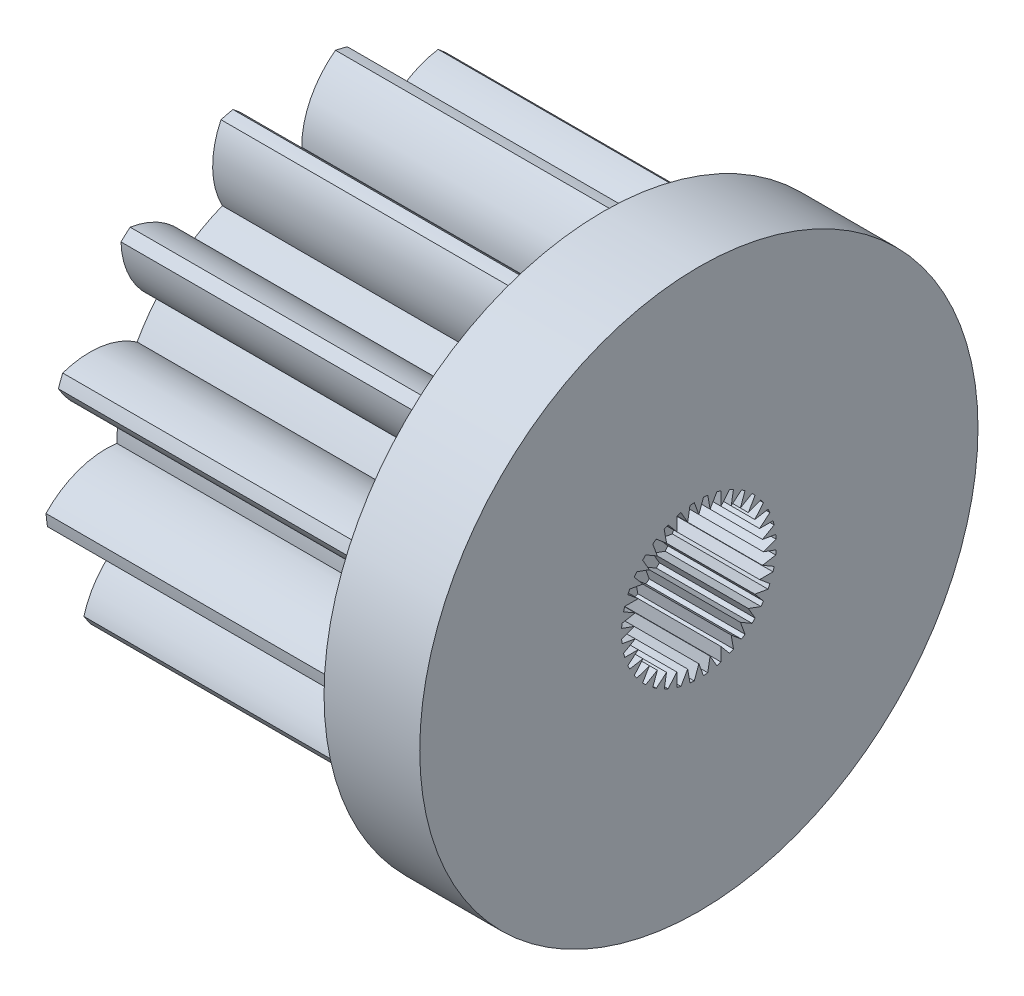
SolidWorks part; units mm, degrees
ref_plane "Front Plane" through (0, 0, 0) normal (0, 0, 1) x (1, 0, 0)
ref_plane "Top Plane" through (0, 0, 0) normal (0, 1, 0) x (1, 0, 0)
ref_plane "Right Plane" through (0, 0, 0) normal (1, 0, 0) x (0, 0, -1)
ref_plane "Plane1" through (0, 0, 0) normal (0, 0, -1) x (-1, 0, 0)
sketch "Sketch1" plane through (0, 0, 0) normal (0, 0, -1) x (-1, 0, 0)
  line L0 (-13, 8.75) -> (-13, 0)
  line L1 (-13, 0) -> (-10, 0)
  line L2 (-10, 0) -> (-10, 8.75)
  line L3 (-10, 8.75) -> (-13, 8.75)
  line L4 (-13, 0) -> (-10, 0) construction
revolve "Revolve1" add sketch "Sketch1" angle 360 about L4
sketch "Sketch2" plane through (10, 0, 0) normal (-1, 0, 0) x (0, 0, 1)
  arc A0 (3.9833, 3.4184) -> (4.6087, 2.5123) centre (0, 0) cw
  arc A1 (4.6087, 2.5123) -> (6.9422, 2.8383) centre (6.0962, 0.3798) cw
  arc A2 (6.9422, 2.8383) -> (7.0785, 2.479) centre (0, 0) cw
  arc A3 (7.0785, 2.479) -> (5.1156, 1.1757) centre (4.8149, 3.7582) cw
  arc A4 (5.1156, 1.1757) -> (5.2483, 0.0827) centre (0, 0) cw
  arc A5 (5.2483, 0.0827) -> (7.466, -0.713) centre (5.5744, -2.4967) cw
  arc A6 (7.466, -0.713) -> (7.4197, -1.0945) centre (0, 0) cw
  arc A7 (7.4197, -1.0945) -> (5.076, -1.3363) centre (6.0099, 1.0901) cw
  arc A8 (5.076, -1.3363) -> (4.6856, -2.3658) centre (0, 0) cw
  arc A9 (4.6856, -2.3658) -> (6.2795, -4.101) centre (3.7756, -4.8013) cw
  arc A10 (6.2795, -4.101) -> (6.0612, -4.4172) centre (0, 0) cw
  arc A11 (6.0612, -4.4172) -> (3.8736, -3.5422) centre (5.8281, -1.8277) cw
  arc A12 (3.8736, -3.5422) -> (3.0495, -4.2723) centre (0, 0) cw
  arc A13 (3.0495, -4.2723) -> (3.6544, -6.5495) centre (1.1118, -6.006) cw
  arc A14 (3.6544, -6.5495) -> (3.3142, -6.728) centre (0, 0) cw
  arc A15 (3.3142, -6.728) -> (1.7837, -4.9366) centre (4.3112, -4.3268) cw
  arc A16 (1.7837, -4.9366) -> (0.7147, -5.2001) centre (0, 0) cw
  arc A17 (0.7147, -5.2001) -> (0.1921, -7.4975) centre (-1.8066, -5.8347) cw
  arc A18 (0.1921, -7.4975) -> (-0.1921, -7.4975) centre (0, 0) cw
  arc A19 (-0.1921, -7.4975) -> (-0.7147, -5.2001) centre (1.8066, -5.8347) cw
  arc A20 (-0.7147, -5.2001) -> (-1.7837, -4.9366) centre (0, 0) cw
  arc A21 (-1.7837, -4.9366) -> (-3.3142, -6.728) centre (-4.3112, -4.3268) cw
  arc A22 (-3.3142, -6.728) -> (-3.6544, -6.5495) centre (0, 0) cw
  arc A23 (-3.6544, -6.5495) -> (-3.0495, -4.2723) centre (-1.1118, -6.006) cw
  arc A24 (-3.0495, -4.2723) -> (-3.8736, -3.5422) centre (0, 0) cw
  arc A25 (-3.8736, -3.5422) -> (-6.0612, -4.4172) centre (-5.8281, -1.8277) cw
  arc A26 (-6.0612, -4.4172) -> (-6.2795, -4.101) centre (0, 0) cw
  arc A27 (-6.2795, -4.101) -> (-4.6856, -2.3658) centre (-3.7756, -4.8013) cw
  arc A28 (-4.6856, -2.3658) -> (-5.076, -1.3363) centre (0, 0) cw
  arc A29 (-5.076, -1.3363) -> (-7.4197, -1.0945) centre (-6.0099, 1.0901) cw
  arc A30 (-7.4197, -1.0945) -> (-7.466, -0.713) centre (0, 0) cw
  arc A31 (-7.466, -0.713) -> (-5.2483, 0.0827) centre (-5.5744, -2.4967) cw
  arc A32 (-5.2483, 0.0827) -> (-5.1156, 1.1757) centre (0, 0) cw
  arc A33 (-5.1156, 1.1757) -> (-7.0785, 2.479) centre (-4.8149, 3.7582) cw
  arc A34 (-7.0785, 2.479) -> (-6.9422, 2.8383) centre (0, 0) cw
  arc A35 (-6.9422, 2.8383) -> (-4.6087, 2.5123) centre (-6.0962, 0.3798) cw
  arc A36 (-4.6087, 2.5123) -> (-3.9833, 3.4184) centre (0, 0) cw
  arc A37 (-3.9833, 3.4184) -> (-5.1156, 5.4846) centre (-2.5169, 5.5654) cw
  arc A38 (-5.1156, 5.4846) -> (-4.828, 5.7394) centre (0, 0) cw
  arc A39 (-4.828, 5.7394) -> (-2.9133, 4.3663) centre (-5.2214, 3.1693) cw
  arc A40 (-2.9133, 4.3663) -> (-1.9384, 4.878) centre (0, 0) cw
  arc A41 (-1.9384, 4.878) -> (-1.9808, 7.2337) centre (0.3578, 6.0975) cw
  arc A42 (-1.9808, 7.2337) -> (-1.6077, 7.3257) centre (0, 0) cw
  arc A43 (-1.6077, 7.3257) -> (-0.5505, 5.2201) centre (-3.1505, 5.2328) cw
  arc A44 (-0.5505, 5.2201) -> (0.5505, 5.2201) centre (0, 0) cw
  arc A45 (0.5505, 5.2201) -> (1.6077, 7.3257) centre (3.1505, 5.2328) cw
  arc A46 (1.6077, 7.3257) -> (1.9808, 7.2337) centre (0, 0) cw
  arc A47 (1.9808, 7.2337) -> (1.9384, 4.878) centre (-0.3578, 6.0975) cw
  arc A48 (1.9384, 4.878) -> (2.9133, 4.3663) centre (0, 0) cw
  arc A49 (2.9133, 4.3663) -> (4.828, 5.7394) centre (5.2214, 3.1693) cw
  arc A50 (4.828, 5.7394) -> (5.1156, 5.4846) centre (0, 0) cw
  arc A51 (5.1156, 5.4846) -> (3.9833, 3.4184) centre (2.5169, 5.5654) cw
extrude "Boss-Extrude1" add sketch "Sketch2" along normal blind 10
sketch "Sketch3" plane through (13, 0, 0) normal (1, 0, 0) x (0, 0, -1)
  line L0 (0, -2.025) -> (0.144, -2.4207)
  line L1 (0.2785, -2.409) -> (0.3516, -1.9942)
  line L2 (0.3516, -1.9942) -> (0.5622, -2.3589)
  line L3 (0.6926, -2.324) -> (0.6926, -1.9029)
  line L4 (0.6926, -1.9029) -> (0.9633, -2.2255)
  line L5 (1.0856, -2.1684) -> (1.0125, -1.7537)
  line L6 (1.0125, -1.7537) -> (1.3351, -2.0244)
  line L7 (1.4457, -1.947) -> (1.3016, -1.5512)
  line L8 (1.3016, -1.5512) -> (1.6663, -1.7618)
  line L9 (1.7618, -1.6663) -> (1.5512, -1.3016)
  line L10 (1.5512, -1.3016) -> (1.947, -1.4457)
  line L11 (2.0244, -1.3351) -> (1.7537, -1.0125)
  line L12 (1.7537, -1.0125) -> (2.1684, -1.0856)
  line L13 (2.2255, -0.9633) -> (1.9029, -0.6926)
  line L14 (1.9029, -0.6926) -> (2.324, -0.6926)
  line L15 (2.3589, -0.5622) -> (1.9942, -0.3516)
  line L16 (1.9942, -0.3516) -> (2.409, -0.2785)
  line L17 (2.4207, -0.144) -> (2.025, 0)
  line L18 (2.025, 0) -> (2.4207, 0.144)
  line L19 (2.409, 0.2785) -> (1.9942, 0.3516)
  line L20 (1.9942, 0.3516) -> (2.3589, 0.5622)
  line L21 (2.324, 0.6926) -> (1.9029, 0.6926)
  line L22 (1.9029, 0.6926) -> (2.2255, 0.9633)
  line L23 (2.1684, 1.0856) -> (1.7537, 1.0125)
  line L24 (1.7537, 1.0125) -> (2.0244, 1.3351)
  line L25 (1.947, 1.4457) -> (1.5512, 1.3016)
  line L26 (1.5512, 1.3016) -> (1.7618, 1.6663)
  line L27 (1.6663, 1.7618) -> (1.3016, 1.5512)
  line L28 (1.3016, 1.5512) -> (1.4457, 1.947)
  line L29 (1.3351, 2.0244) -> (1.0125, 1.7537)
  line L30 (1.0125, 1.7537) -> (1.0856, 2.1684)
  line L31 (0.9633, 2.2255) -> (0.6926, 1.9029)
  line L32 (0.6926, 1.9029) -> (0.6926, 2.324)
  line L33 (0.5622, 2.3589) -> (0.3516, 1.9942)
  line L34 (0.3516, 1.9942) -> (0.2785, 2.409)
  line L35 (0.144, 2.4207) -> (0, 2.025)
  line L36 (0, 2.025) -> (-0.144, 2.4207)
  line L37 (-0.2785, 2.409) -> (-0.3516, 1.9942)
  line L38 (-0.3516, 1.9942) -> (-0.5622, 2.3589)
  line L39 (-0.6926, 2.324) -> (-0.6926, 1.9029)
  line L40 (-0.6926, 1.9029) -> (-0.9633, 2.2255)
  line L41 (-1.0856, 2.1684) -> (-1.0125, 1.7537)
  line L42 (-1.0125, 1.7537) -> (-1.3351, 2.0244)
  line L43 (-1.4457, 1.947) -> (-1.3016, 1.5512)
  line L44 (-1.3016, 1.5512) -> (-1.6663, 1.7618)
  line L45 (-1.7618, 1.6663) -> (-1.5512, 1.3016)
  line L46 (-1.5512, 1.3016) -> (-1.947, 1.4457)
  line L47 (-2.0244, 1.3351) -> (-1.7537, 1.0125)
  line L48 (-1.7537, 1.0125) -> (-2.1684, 1.0856)
  line L49 (-2.2255, 0.9633) -> (-1.9029, 0.6926)
  line L50 (-1.9029, 0.6926) -> (-2.324, 0.6926)
  line L51 (-2.3589, 0.5622) -> (-1.9942, 0.3516)
  line L52 (-1.9942, 0.3516) -> (-2.409, 0.2785)
  line L53 (-2.4207, 0.144) -> (-2.025, 0)
  line L54 (-2.025, 0) -> (-2.4207, -0.144)
  line L55 (-2.409, -0.2785) -> (-1.9942, -0.3516)
  line L56 (-1.9942, -0.3516) -> (-2.3589, -0.5622)
  line L57 (-2.324, -0.6926) -> (-1.9029, -0.6926)
  line L58 (-1.9029, -0.6926) -> (-2.2255, -0.9633)
  line L59 (-2.1684, -1.0856) -> (-1.7537, -1.0125)
  line L60 (-1.7537, -1.0125) -> (-2.0244, -1.3351)
  line L61 (-1.947, -1.4457) -> (-1.5512, -1.3016)
  line L62 (-1.5512, -1.3016) -> (-1.7618, -1.6663)
  line L63 (-1.6663, -1.7618) -> (-1.3016, -1.5512)
  line L64 (-1.3016, -1.5512) -> (-1.4457, -1.947)
  line L65 (-1.3351, -2.0244) -> (-1.0125, -1.7537)
  line L66 (-1.0125, -1.7537) -> (-1.0856, -2.1684)
  line L67 (-0.9633, -2.2255) -> (-0.6926, -1.9029)
  line L68 (-0.6926, -1.9029) -> (-0.6926, -2.324)
  line L69 (-0.5622, -2.3589) -> (-0.3516, -1.9942)
  line L70 (-0.3516, -1.9942) -> (-0.2785, -2.409)
  line L71 (-0.144, -2.4207) -> (0, -2.025)
  arc A0 (0.144, -2.4207) -> (0.2785, -2.409) centre (0, 0) ccw
  arc A1 (0.5622, -2.3589) -> (0.6926, -2.324) centre (0, 0) ccw
  arc A2 (0.9633, -2.2255) -> (1.0856, -2.1684) centre (0, 0) ccw
  arc A3 (1.3351, -2.0244) -> (1.4457, -1.947) centre (0, 0) ccw
  arc A4 (1.6663, -1.7618) -> (1.7618, -1.6663) centre (0, 0) ccw
  arc A5 (1.947, -1.4457) -> (2.0244, -1.3351) centre (0, 0) ccw
  arc A6 (2.1684, -1.0856) -> (2.2255, -0.9633) centre (0, 0) ccw
  arc A7 (2.324, -0.6926) -> (2.3589, -0.5622) centre (0, 0) ccw
  arc A8 (2.409, -0.2785) -> (2.4207, -0.144) centre (0, 0) ccw
  arc A9 (2.4207, 0.144) -> (2.409, 0.2785) centre (0, 0) ccw
  arc A10 (2.3589, 0.5622) -> (2.324, 0.6926) centre (0, 0) ccw
  arc A11 (2.2255, 0.9633) -> (2.1684, 1.0856) centre (0, 0) ccw
  arc A12 (2.0244, 1.3351) -> (1.947, 1.4457) centre (0, 0) ccw
  arc A13 (1.7618, 1.6663) -> (1.6663, 1.7618) centre (0, 0) ccw
  arc A14 (1.4457, 1.947) -> (1.3351, 2.0244) centre (0, 0) ccw
  arc A15 (1.0856, 2.1684) -> (0.9633, 2.2255) centre (0, 0) ccw
  arc A16 (0.6926, 2.324) -> (0.5622, 2.3589) centre (0, 0) ccw
  arc A17 (0.2785, 2.409) -> (0.144, 2.4207) centre (0, 0) ccw
  arc A18 (-0.144, 2.4207) -> (-0.2785, 2.409) centre (0, 0) ccw
  arc A19 (-0.5622, 2.3589) -> (-0.6926, 2.324) centre (0, 0) ccw
  arc A20 (-0.9633, 2.2255) -> (-1.0856, 2.1684) centre (0, 0) ccw
  arc A21 (-1.3351, 2.0244) -> (-1.4457, 1.947) centre (0, 0) ccw
  arc A22 (-1.6663, 1.7618) -> (-1.7618, 1.6663) centre (0, 0) ccw
  arc A23 (-1.947, 1.4457) -> (-2.0244, 1.3351) centre (0, 0) ccw
  arc A24 (-2.1684, 1.0856) -> (-2.2255, 0.9633) centre (0, 0) ccw
  arc A25 (-2.324, 0.6926) -> (-2.3589, 0.5622) centre (0, 0) ccw
  arc A26 (-2.409, 0.2785) -> (-2.4207, 0.144) centre (0, 0) ccw
  arc A27 (-2.4207, -0.144) -> (-2.409, -0.2785) centre (0, 0) ccw
  arc A28 (-2.3589, -0.5622) -> (-2.324, -0.6926) centre (0, 0) ccw
  arc A29 (-2.2255, -0.9633) -> (-2.1684, -1.0856) centre (0, 0) ccw
  arc A30 (-2.0244, -1.3351) -> (-1.947, -1.4457) centre (0, 0) ccw
  arc A31 (-1.7618, -1.6663) -> (-1.6663, -1.7618) centre (0, 0) ccw
  arc A32 (-1.4457, -1.947) -> (-1.3351, -2.0244) centre (0, 0) ccw
  arc A33 (-1.0856, -2.1684) -> (-0.9633, -2.2255) centre (0, 0) ccw
  arc A34 (-0.6926, -2.324) -> (-0.5622, -2.3589) centre (0, 0) ccw
  arc A35 (-0.2785, -2.409) -> (-0.144, -2.4207) centre (0, 0) ccw
extrude "Cut-Extrude1" cut sketch "Sketch3" against normal blind 3
hole_wizard "Ø1.6 (1.6) Diameter Hole1" positions "Sketch5" profile "Sketch4" hole size "Ø1.6" standard "ANSI Metric"
sketch "Sketch5" plane through (0, 0, 0) normal (-1, 0, 0) x (0, 0, 1)
  point P0 (0, 0)
sketch "Sketch4" plane through (0, 0, 0) normal (0, 1, 0) x (0, 0, 1)
  line L0 (0, 0) -> (0, 13)
  line L1 (0, 13) -> (0.8, 13)
  line L2 (0.8, 13) -> (0.8, 0)
  line L5 (0.8, 0) -> (0, 0)
  line L11 (0, -6.35) -> (0, 107.95) construction
  dimension "Thru Hole Dia." = 1.6
  dimension "Thru Hole Depth" = 13
